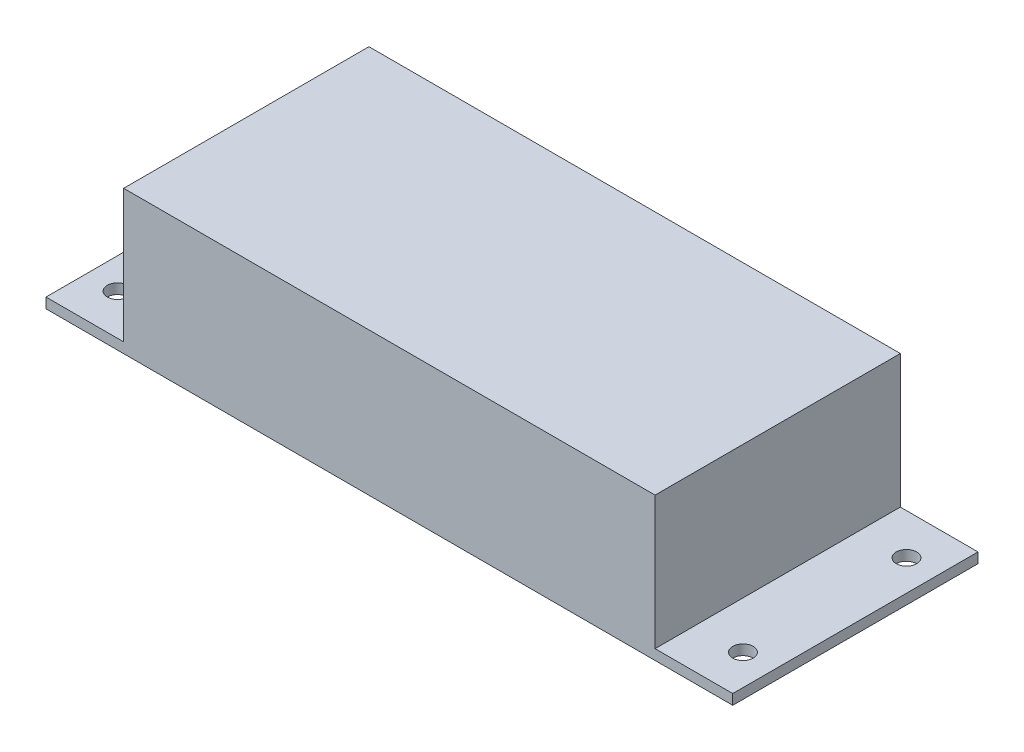
SolidWorks part; units mm, degrees
ref_plane "Front Plane" through (0, 0, 0) normal (0, 0, 1) x (1, 0, 0)
ref_plane "Top Plane" through (0, 0, 0) normal (0, 1, 0) x (1, 0, 0)
ref_plane "Right Plane" through (0, 0, 0) normal (1, 0, 0) x (0, 0, -1)
sketch "Sketch1" plane through (0, 0, 0) normal (0, 1, 0) x (1, 0, 0)
  line L1 (-41.275, -19.05) -> (41.275, -19.05)
  line L2 (-41.275, -19.05) -> (-41.275, 19.05)
  line L3 (-41.275, 19.05) -> (41.275, 19.05)
  line L4 (41.275, -19.05) -> (41.275, 19.05)
  line L5 (-41.275, -19.05) -> (41.275, 19.05) construction
  line L6 (-41.275, 19.05) -> (41.275, -19.05) construction
  point P0 (0, 0)
  dimension "D1" = 38.1
  dimension "D2" = 82.55
extrude "Boss-Extrude1" add sketch "Sketch1" along normal blind 22.2504
sketch "Sketch2" plane through (0, 0, 0) normal (0, 1, 0) x (1, 0, 0)
  line L0 (-41.275, 19.05) -> (-41.275, -19.05) construction
  line L1 (-53.34, -19.05) -> (53.34, -19.05)
  line L2 (-53.34, -19.05) -> (-53.34, 19.05)
  line L3 (-53.34, 19.05) -> (53.34, 19.05)
  line L4 (53.34, -19.05) -> (53.34, 19.05)
  line L5 (-53.34, -19.05) -> (53.34, 19.05) construction
  line L6 (-53.34, 19.05) -> (53.34, -19.05) construction
  line L7 (-53.34, 0) -> (53.34, 0) construction
  line L8 (0, 19.05) -> (0, -19.05) construction
  circle A0 centre (-48.5775, 12.7) radius 1.5875
  circle A1 centre (48.5775, 12.7) radius 1.5875
  circle A2 centre (48.5775, -12.7) radius 1.5875
  circle A3 centre (-48.5775, -12.7) radius 1.5875
  point P0 (0, 0)
  dimension "D4" = 3.175
  dimension "D1" = 106.68
  dimension "D2" = 4.7625
  dimension "D3" = 6.35
extrude "Boss-Extrude2" add sketch "Sketch2" along normal blind 1.5875 contours L2 L3 L4 L1 | A3 | A1 | A2 | A0
